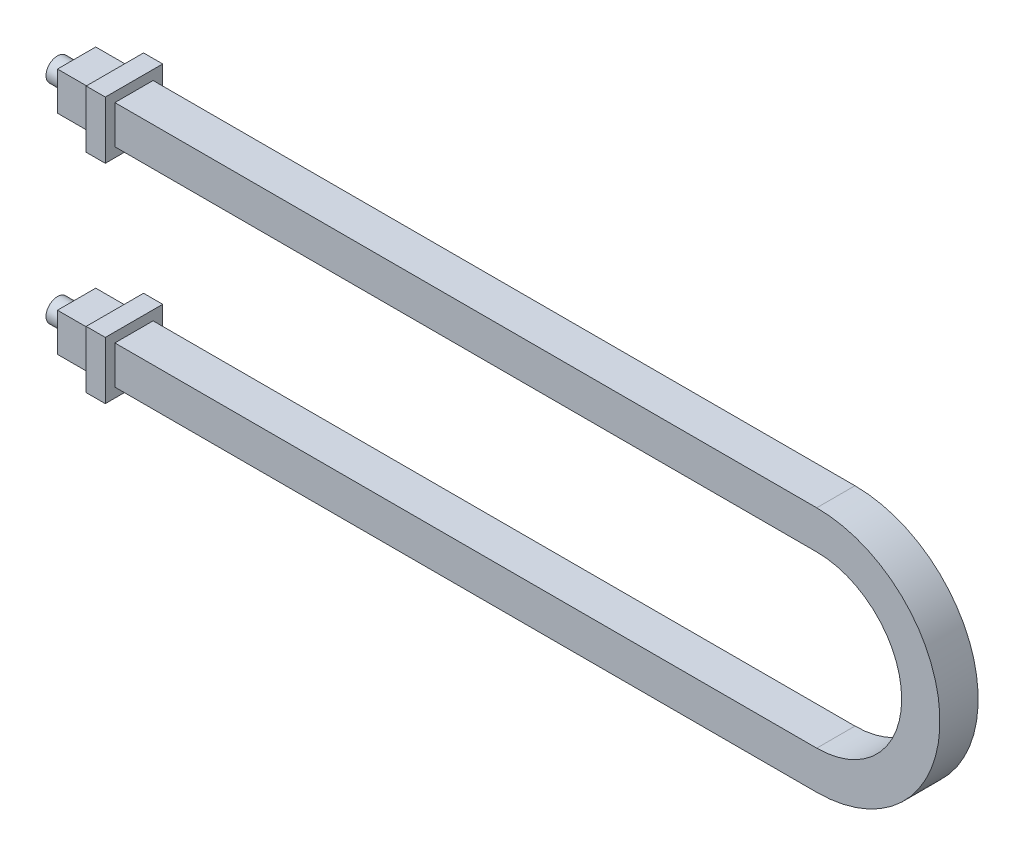
SolidWorks part; units mm, degrees
ref_plane "Alzado" through (0, 0, 0) normal (0, 0, 1) x (1, 0, 0)
ref_plane "Planta" through (0, 0, 0) normal (0, 1, 0) x (1, 0, 0)
ref_plane "Vista lateral" through (0, 0, 0) normal (1, 0, 0) x (0, 0, -1)
sketch "Sketch1" plane through (0, 0, 0) normal (0, 0, 1) x (1, 0, 0)
  line L0 (0, 0) -> (188.4679, 0)
  line L1 (188.4679, -64.4097) -> (0, -64.4097)
  line L2 (0, -10) -> (188.4679, -10)
  line L3 (188.4679, -54.4097) -> (0, -54.4097)
  line L4 (0, -10) -> (0, 0)
  line L5 (0, -54.4097) -> (0, -64.4097)
  arc A0 (188.4679, 0) -> (188.4679, -64.4097) centre (188.4679, -32.2048) cw
  arc A1 (188.4679, -10) -> (188.4679, -54.4097) centre (188.4679, -32.2048) cw
  dimension "D1" = 32.2048
  dimension "D3" = 10
  dimension "D2" = 188.4679
extrude "Boss-Extrude1" add sketch "Sketch1" along normal blind 10
sketch "Sketch2" plane through (0, 0, 0) normal (-1, 0, 0) x (0, 0, 1)
  line L0 (5, 0) -> (5, -10) construction
  line L1 (10, 0) -> (0, 0) construction
  line L2 (10, -10) -> (0, -10) construction
  circle A0 centre (5, -4.907) radius 3
  dimension "D1" = 6
extrude "Boss-Extrude2" add sketch "Sketch2" along normal blind 15
sketch "Sketch3" plane through (0, 0, 0) normal (-1, 0, 0) x (0, 0, 1)
  line L0 (5, -54.4097) -> (5, -64.4097) construction
  line L1 (10, -54.4097) -> (0, -54.4097) construction
  line L2 (10, -64.4097) -> (0, -64.4097) construction
  circle A0 centre (5, -59.4097) radius 3
  dimension "D1" = 6
extrude "Boss-Extrude3" add sketch "Sketch3" along normal blind 15 separate body
sketch "Sketch5" plane through (0, 0, 0) normal (1, 0, 0) x (0, 0, -1)
  line L0 (-5, 0) -> (-5, -64.4097) construction
  line L1 (-10, 0) -> (0, 0) construction
  line L2 (-10, -64.4097) -> (0, -64.4097) construction
  line L3 (0, -5) -> (-10, -5) construction
  line L4 (0, 0) -> (0, -10) construction
  line L5 (-10, 0) -> (-10, -10) construction
  line L6 (0, -32.2048) -> (-10, -32.2048) construction
  line L7 (-10, -10) -> (-10, -54.4097) construction
  line L8 (2.5, -51.9097) -> (-12.5, -51.9097)
  line L9 (2.5, 2.5) -> (-12.5, 2.5)
  line L10 (2.5, 2.5) -> (2.5, -12.5)
  line L11 (2.5, -12.5) -> (-12.5, -12.5)
  line L12 (-12.5, 2.5) -> (-12.5, -12.5)
  line L13 (2.5, 2.5) -> (-12.5, -12.5) construction
  line L14 (2.5, -12.5) -> (-12.5, 2.5) construction
  line L15 (-12.5, -66.9097) -> (-12.5, -51.9097)
  line L16 (2.5, -66.9097) -> (-12.5, -66.9097)
  line L17 (2.5, -66.9097) -> (2.5, -51.9097)
  point P12 (-5, -5)
  point P17 (-5, -32.2048)
  dimension "D1" = 15
  dimension "D2" = 15
extrude "Boss-Extrude4" add sketch "Sketch5" along normal blind 5 separate body
sketch "Sketch7" plane through (0, 0, 0) normal (-1, 0, 0) x (0, 0, 1)
  line L0 (5, 2.5) -> (5, -66.9097) construction
  line L1 (-2.5, 2.5) -> (12.5, 2.5) construction
  line L2 (12.5, -66.9097) -> (-2.5, -66.9097) construction
  line L3 (0, -32.2048) -> (10, -32.2048) construction
  line L4 (10, -54.4097) -> (10, -10) construction
  line L5 (-2.5, -5) -> (12.5, -5) construction
  line L6 (-2.5, -12.5) -> (-2.5, 2.5) construction
  line L7 (12.5, 2.5) -> (12.5, -12.5) construction
  line L8 (0, -54.5027) -> (10, -54.5027)
  line L9 (0, 0.093) -> (10, 0.093)
  line L10 (0, 0.093) -> (0, -9.907)
  line L11 (0, -9.907) -> (10, -9.907)
  line L12 (10, 0.093) -> (10, -9.907)
  line L13 (0, 0.093) -> (10, -9.907) construction
  line L14 (0, -9.907) -> (10, 0.093) construction
  line L15 (10, -64.5027) -> (10, -54.5027)
  line L16 (0, -64.5027) -> (10, -64.5027)
  line L17 (0, -64.5027) -> (0, -54.5027)
  point P11 (5, -32.2048)
  point P17 (5, -4.907)
  dimension "D1" = 10
  dimension "D2" = 10
extrude "Boss-Extrude5" add sketch "Sketch7" along normal blind 10
